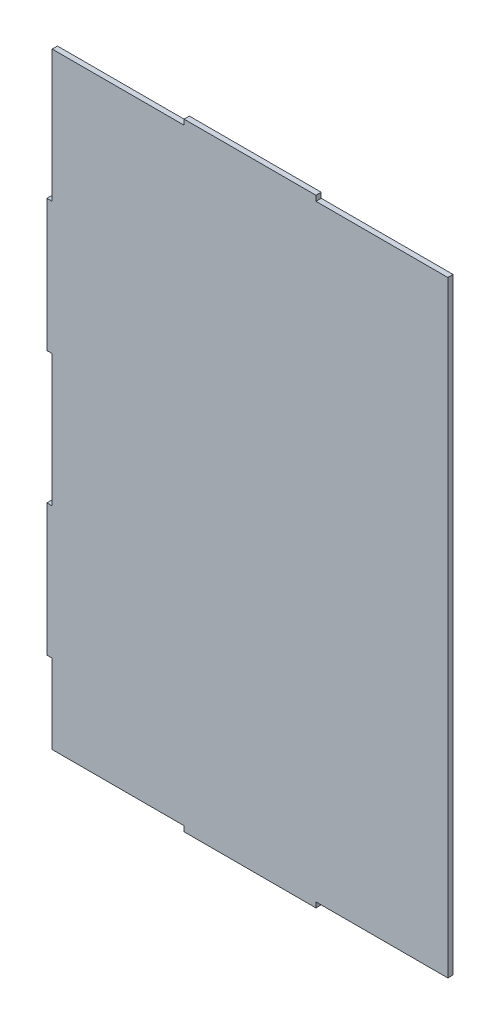
SolidWorks part; units mm, degrees
ref_plane "前视基准面" through (0, 0, 0) normal (0, 0, 1) x (1, 0, 0)
ref_plane "上视基准面" through (0, 0, 0) normal (0, 1, 0) x (1, 0, 0)
ref_plane "右视基准面" through (0, 0, 0) normal (1, 0, 0) x (0, 0, -1)
other "Configuration Table"
sketch "草图1" plane through (0, 0, 0) normal (0, 0, 1) x (1, 0, 0)
  line L0 (323.4631, 208.1679) -> (327.4631, 208.1679)
  line L1 (323.4631, 308.1679) -> (323.4631, 208.1679)
  line L2 (327.4631, 308.1679) -> (323.4631, 308.1679)
  line L3 (327.4631, 408.1679) -> (327.4631, 308.1679)
  line L4 (323.4631, 408.1679) -> (327.4631, 408.1679)
  line L5 (323.4631, 508.1679) -> (323.4631, 408.1679)
  line L6 (327.4631, 508.1679) -> (323.4631, 508.1679)
  line L7 (327.4631, 608.1679) -> (327.4631, 508.1679)
  line L8 (627.4631, 608.1679) -> (527.4631, 608.1679)
  line L9 (427.4631, 608.1679) -> (327.4631, 608.1679)
  line L10 (627.4631, 508.1679) -> (627.4631, 608.1679)
  line L12 (627.4631, 148.1679) -> (627.4631, 208.1679)
  line L13 (527.4631, 148.1679) -> (627.4631, 148.1679)
  line L14 (527.4631, 144.1679) -> (527.4631, 148.1679)
  line L15 (427.4631, 144.1679) -> (527.4631, 144.1679)
  line L16 (427.4631, 148.1679) -> (427.4631, 144.1679)
  line L17 (327.4631, 148.1679) -> (427.4631, 148.1679)
  line L18 (327.4631, 208.1679) -> (327.4631, 148.1679)
  line L24 (527.4631, 612.1679) -> (527.4631, 608.1679)
  line L25 (427.4631, 612.1679) -> (527.4631, 612.1679)
  line L26 (427.4631, 608.1679) -> (427.4631, 612.1679)
  line L28 (627.4631, 508.1679) -> (627.4631, 208.1679)
extrude "凸台-拉伸1" add sketch "草图1" along normal blind 4
